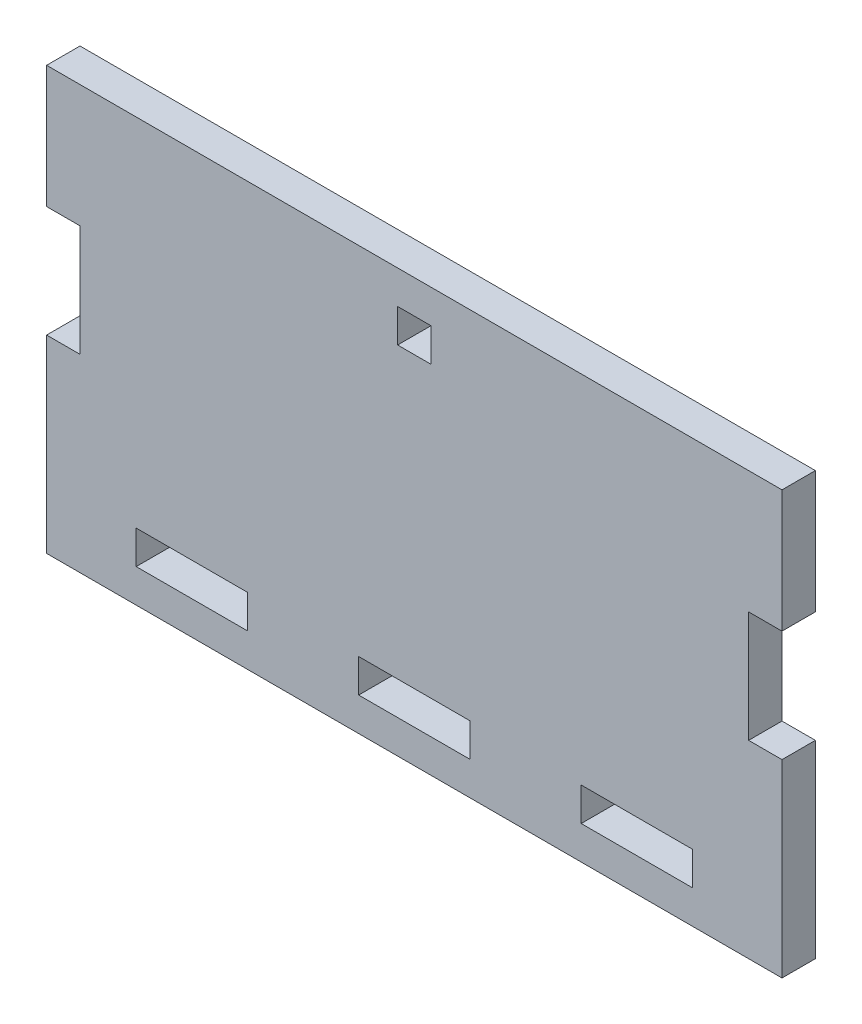
SolidWorks part; units mm, degrees
ref_plane "Front Plane" through (0, 0, 0) normal (0, 0, 1) x (1, 0, 0)
ref_plane "Top Plane" through (0, 0, 0) normal (0, 1, 0) x (1, 0, 0)
ref_plane "Right Plane" through (0, 0, 0) normal (1, 0, 0) x (0, 0, -1)
sketch "Sketch1" plane through (0, 0, 0) normal (0, 0, 1) x (1, 0, 0)
  line L0 (-28.0561, 24.8093) -> (-28.0561, -22.86) construction
  line L1 (-61.1061, 24.8093) -> (4.9939, 24.8093)
  line L2 (-61.1061, 24.8093) -> (-61.1061, -13.1907)
  line L3 (-61.1061, -13.1907) -> (4.9939, -13.1907)
  line L4 (4.9939, 24.8093) -> (4.9939, -13.1907)
  line L5 (4.9939, 13.8093) -> (1.9939, 13.8093)
  line L6 (1.9939, 13.8093) -> (1.9939, 3.8093)
  line L7 (1.9939, 3.8093) -> (4.9939, 3.8093)
  line L8 (-33.0561, -10.1907) -> (-23.0561, -10.1907)
  line L9 (-3.0561, -7.1907) -> (-13.0561, -7.1907)
  line L10 (-3.0561, -7.1907) -> (-3.0561, -10.1907)
  line L11 (-3.0561, -10.1907) -> (-13.0561, -10.1907)
  line L12 (-13.0561, -7.1907) -> (-13.0561, -10.1907)
  line L13 (-29.5561, 21.8093) -> (-26.5561, 21.8093)
  line L14 (-26.5561, 21.8093) -> (-26.5561, 18.8093)
  line L15 (-26.5561, 18.8093) -> (-29.5561, 18.8093)
  line L16 (-29.5561, 21.8093) -> (-29.5561, 18.8093)
  line L17 (-23.0561, -10.1907) -> (-23.0561, -7.1907)
  line L18 (-23.0561, -7.1907) -> (-33.0561, -7.1907)
  line L19 (-33.0561, -10.1907) -> (-33.0561, -7.1907)
  line L20 (-43.0561, -7.1907) -> (-43.0561, -10.1907)
  line L21 (-53.0561, -10.1907) -> (-43.0561, -10.1907)
  line L22 (-53.0561, -7.1907) -> (-53.0561, -10.1907)
  line L23 (-53.0561, -7.1907) -> (-43.0561, -7.1907)
  line L24 (-58.1061, 3.8093) -> (-61.1061, 3.8093)
  line L25 (-58.1061, 13.8093) -> (-58.1061, 3.8093)
  line L26 (-61.1061, 13.8093) -> (-58.1061, 13.8093)
  point P22 (-28.0561, -10.1907)
  point P24 (-28.0561, -7.1907)
  point P33 (-28.0561, 18.8093)
  point P34 (-28.0561, 21.8093)
  dimension "D1" = 66.1
  dimension "D2" = 38
  dimension "D3" = 3
  dimension "D4" = 10
  dimension "D5" = 11
  dimension "D6" = 17
  dimension "D7" = 10
  dimension "D8" = 3
  dimension "D9" = 8.05
  dimension "D10" = 3
  dimension "D11" = 3
  dimension "D12" = 1.5
  dimension "D13" = 3
  dimension "D15" = 5
  dimension "D16" = 3
  dimension "D17" = 3
extrude "Boss-Extrude1" add sketch "Sketch1" along normal blind 3 contours L0 L1 L2 L26 L25 L24 L3 L8 L19 L18 L22 L23 L20 L21 | L1 L0 L18 L17 L8 L3 L4 L7 L6 L5 L12 L9 L10 L11
